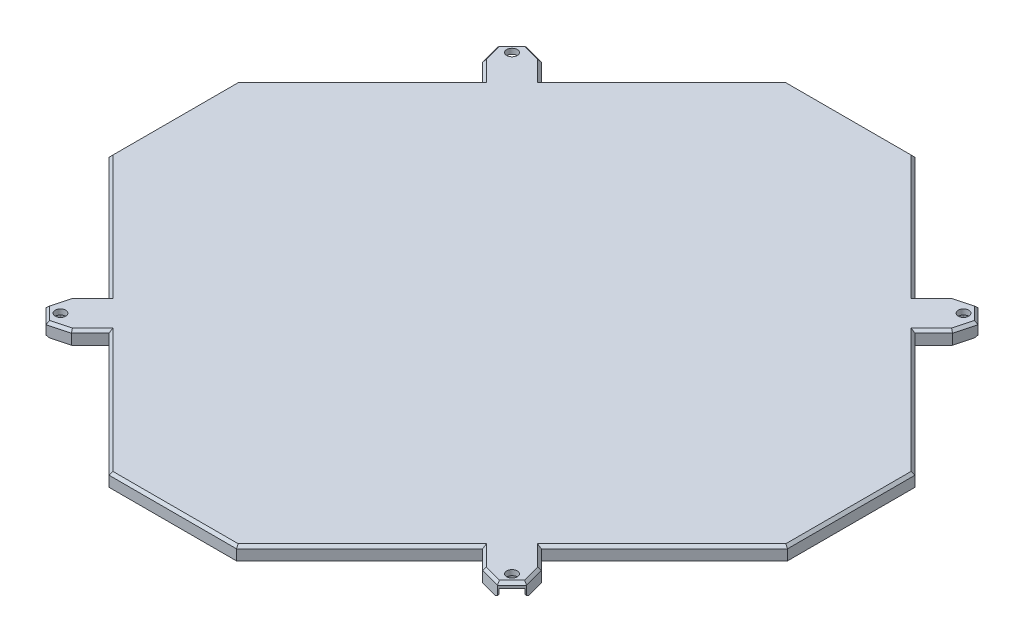
SolidWorks part; units mm, degrees
ref_plane "Front Plane" through (0, 0, 0) normal (0, 0, 1) x (1, 0, 0)
ref_plane "Top Plane" through (0, 0, 0) normal (0, 1, 0) x (1, 0, 0)
ref_plane "Right Plane" through (0, 0, 0) normal (1, 0, 0) x (0, 0, -1)
sketch "Floor Reference" plane through (0, 0, 0) normal (0, 1, 0) x (-1, 0, 0)
  line L0 (-129.3223, 24.3223) -> (-82.4792, 71.1655)
  line L1 (-82.4792, 71.1655) -> (-89.601, 78.2873)
  line L2 (-89.601, 78.2873) -> (-91.6716, 86.0147)
  line L3 (-91.6716, 86.0147) -> (-86.0147, 91.6716)
  line L4 (-86.0147, 91.6716) -> (-78.2873, 89.601)
  line L5 (-78.2873, 89.601) -> (-71.1655, 82.4792)
  line L6 (-71.1655, 82.4792) -> (-24.3223, 129.3223)
  line L7 (-24.3223, 129.3223) -> (0, 129.3223)
  line L31 (-129.3223, 0) -> (-129.3223, 24.3223)
  line L32 (0, 0) -> (-35355.3391, 35355.3391) construction
  line L34 (-1000, 0) -> (0, 0) construction
  line L35 (0, 0) -> (0, 49000) construction
  circle A0 centre (-86.0147, 86.0147) radius 2
  point P8 (0, 0)
  point P14 (0, 0)
  point P18 (-88.8431, 88.8431)
  dimension "D11" = 4
  dimension "D1" = 105
  dimension "D2" = 45
  dimension "D3" = 129.3223
  dimension "D4" = 8
  dimension "D5" = 16
  dimension "D6" = 17
  dimension "D7" = 8
  dimension "D8" = 13
  dimension "D9" = 105
  dimension "D10" = 24.3223
sketch "Sketch2" plane through (0, 0, 0) normal (0, 1, 0) x (1, 0, 0)
  line L0 (129.3223, 0) -> (129.3223, -24.3223) construction
  line L1 (129.3223, -24.3223) -> (82.4792, -71.1655) construction
  line L2 (82.4792, -71.1655) -> (89.601, -78.2873) construction
  line L3 (89.601, -78.2873) -> (91.6716, -86.0147) construction
  line L4 (91.6716, -86.0147) -> (86.0147, -91.6716) construction
  line L5 (86.0147, -91.6716) -> (78.2873, -89.601) construction
  line L6 (78.2873, -89.601) -> (71.1655, -82.4792) construction
  line L7 (71.1655, -82.4792) -> (24.3223, -129.3223) construction
  line L8 (24.3223, -129.3223) -> (0, -129.3223) construction
  line L9 (129.3223, 0) -> (129.3223, -24.3223) construction
  line L10 (129.3223, -24.3223) -> (82.4792, -71.1655) construction
  line L11 (82.4792, -71.1655) -> (89.601, -78.2873) construction
  line L12 (89.601, -78.2873) -> (91.6716, -86.0147) construction
  line L13 (91.6716, -86.0147) -> (86.0147, -91.6716) construction
  line L14 (86.0147, -91.6716) -> (78.2873, -89.601) construction
  line L15 (78.2873, -89.601) -> (71.1655, -82.4792) construction
  line L16 (71.1655, -82.4792) -> (24.3223, -129.3223) construction
  line L17 (24.3223, -129.3223) -> (0, -129.3223) construction
  line L18 (-129.3223, -24.3223) -> (-129.3223, 0) construction
  line L19 (-82.4792, -71.1655) -> (-129.3223, -24.3223) construction
  line L20 (-89.601, -78.2873) -> (-82.4792, -71.1655) construction
  line L21 (-91.6716, -86.0147) -> (-89.601, -78.2873) construction
  line L22 (-86.0147, -91.6716) -> (-91.6716, -86.0147) construction
  line L23 (-78.2873, -89.601) -> (-86.0147, -91.6716) construction
  line L24 (-71.1655, -82.4792) -> (-78.2873, -89.601) construction
  line L25 (-24.3223, -129.3223) -> (-71.1655, -82.4792) construction
  line L26 (0, -129.3223) -> (-24.3223, -129.3223) construction
  line L27 (-24.3223, 129.3223) -> (0, 129.3223) construction
  line L28 (-71.1655, 82.4792) -> (-24.3223, 129.3223) construction
  line L29 (-78.2873, 89.601) -> (-71.1655, 82.4792) construction
  line L30 (-86.0147, 91.6716) -> (-78.2873, 89.601) construction
  line L31 (-91.6716, 86.0147) -> (-86.0147, 91.6716) construction
  line L32 (-89.601, 78.2873) -> (-91.6716, 86.0147) construction
  line L33 (-82.4792, 71.1655) -> (-89.601, 78.2873) construction
  line L34 (-129.3223, 24.3223) -> (-82.4792, 71.1655) construction
  line L35 (-129.3223, 0) -> (-129.3223, 24.3223) construction
  line L36 (129.3223, 24.3223) -> (129.3223, 0) construction
  line L37 (82.4792, 71.1655) -> (129.3223, 24.3223) construction
  line L38 (89.601, 78.2873) -> (82.4792, 71.1655) construction
  line L39 (91.6716, 86.0147) -> (89.601, 78.2873) construction
  line L40 (86.0147, 91.6716) -> (91.6716, 86.0147) construction
  line L41 (78.2873, 89.601) -> (86.0147, 91.6716) construction
  line L42 (71.1655, 82.4792) -> (78.2873, 89.601) construction
  line L43 (24.3223, 129.3223) -> (71.1655, 82.4792) construction
  line L44 (0, 129.3223) -> (24.3223, 129.3223) construction
  line L45 (129.2223, 0) -> (129.2223, -24.2809)
  line L46 (129.2223, -24.2809) -> (82.3378, -71.1655)
  line L47 (82.3378, -71.1655) -> (89.5114, -78.3391)
  line L48 (89.5114, -78.3391) -> (91.56, -85.9848)
  line L49 (91.56, -85.9848) -> (85.9848, -91.56)
  line L50 (85.9848, -91.56) -> (78.3391, -89.5114)
  line L51 (78.3391, -89.5114) -> (71.1655, -82.3378)
  line L52 (71.1655, -82.3378) -> (24.2809, -129.2223)
  line L53 (24.2809, -129.2223) -> (0, -129.2223)
  line L54 (0, -129.2223) -> (-24.2809, -129.2223)
  line L55 (-24.2809, -129.2223) -> (-71.1655, -82.3378)
  line L56 (-71.1655, -82.3378) -> (-78.3391, -89.5114)
  line L57 (-78.3391, -89.5114) -> (-85.9848, -91.56)
  line L58 (-85.9848, -91.56) -> (-91.56, -85.9848)
  line L59 (-91.56, -85.9848) -> (-89.5114, -78.3391)
  line L60 (-89.5114, -78.3391) -> (-82.3378, -71.1655)
  line L61 (-82.3378, -71.1655) -> (-129.2223, -24.2809)
  line L62 (-129.2223, -24.2809) -> (-129.2223, 0)
  line L63 (-129.2223, 0) -> (-129.2223, 24.2809)
  line L64 (-129.2223, 24.2809) -> (-82.3378, 71.1655)
  line L65 (-82.3378, 71.1655) -> (-89.5114, 78.3391)
  line L66 (-89.5114, 78.3391) -> (-91.56, 85.9848)
  line L67 (-91.56, 85.9848) -> (-85.9848, 91.56)
  line L68 (-85.9848, 91.56) -> (-78.3391, 89.5114)
  line L69 (-78.3391, 89.5114) -> (-71.1655, 82.3378)
  line L70 (-71.1655, 82.3378) -> (-24.2809, 129.2223)
  line L71 (-24.2809, 129.2223) -> (0, 129.2223)
  line L72 (0, 129.2223) -> (24.2809, 129.2223)
  line L73 (24.2809, 129.2223) -> (71.1655, 82.3378)
  line L74 (71.1655, 82.3378) -> (78.3391, 89.5114)
  line L75 (78.3391, 89.5114) -> (85.9848, 91.56)
  line L76 (85.9848, 91.56) -> (91.56, 85.9848)
  line L77 (91.56, 85.9848) -> (89.5114, 78.3391)
  line L78 (89.5114, 78.3391) -> (82.3378, 71.1655)
  line L79 (82.3378, 71.1655) -> (129.2223, 24.2809)
  line L80 (129.2223, 24.2809) -> (129.2223, 0)
  circle A0 centre (86.0147, -86.0147) radius 2 construction
  circle A1 centre (86.0147, -86.0147) radius 2
  circle A2 centre (-86.0147, -86.0147) radius 2
  circle A3 centre (-86.0147, 86.0147) radius 2
  circle A4 centre (86.0147, 86.0147) radius 2
  point P13 (0, 0)
  point P54 (0, 0)
  dimension "D2" = 0.1
  dimension "D1" = 4
extrude "Main Floor Extrude" add sketch "Sketch2" along normal blind 5
chamfer "Main Floor Chamfer" distance 1 angle 45 32 edges at (-74.7523, 5, -85.9246) (-82.162, 5, -90.5357) (-88.7724, 5, -88.7724) (-90.5357, 5, -82.162) (-85.9246, 5, -74.7523) (-47.7232, 5, -105.78) (0, 5, -129.2223) (47.7232, 5, -105.78) (74.7523, 5, -85.9246) (82.162, 5, -90.5357) (88.7724, 5, -88.7724) (90.5357, 5, -82.162) (85.9246, 5, -74.7523) (105.78, 5, -47.7232) (129.2223, 5, 0) (105.78, 5, 47.7232) (85.9246, 5, 74.7523) (90.5357, 5, 82.162) (88.7724, 5, 88.7724) (82.162, 5, 90.5357) (74.7523, 5, 85.9246) (47.7232, 5, 105.78) (0, 5, 129.2223) (-47.7232, 5, 105.78) (-74.7523, 5, 85.9246) (-82.162, 5, 90.5357) (-88.7724, 5, 88.7724) (-90.5357, 5, 82.162) (-85.9246, 5, 74.7523) (-105.78, 5, 47.7232) (-129.2223, 5, 0) (-105.78, 5, -47.7232)
sketch "Sketch3" plane through (0, 0, 0) normal (0, -1, 0) x (-1, 0, 0)
  line L0 (91.2473, -86.2976) -> (88.4896, -83.5398)
  line L1 (91.56, -85.9848) -> (85.9848, -91.56) construction
  line L2 (83.5398, -88.4896) -> (86.2976, -91.2473)
  line L3 (86.2976, -91.2473) -> (91.2473, -86.2976)
  line L4 (-86.2976, -91.2473) -> (-83.5398, -88.4896)
  line L5 (-88.4896, -83.5398) -> (-91.2473, -86.2976)
  line L6 (-91.2473, -86.2976) -> (-86.2976, -91.2473)
  line L7 (-91.2473, 86.2976) -> (-88.4896, 83.5398)
  line L8 (-83.5398, 88.4896) -> (-86.2976, 91.2473)
  line L9 (-86.2976, 91.2473) -> (-91.2473, 86.2976)
  line L10 (86.2976, 91.2473) -> (83.5398, 88.4896)
  line L11 (88.4896, 83.5398) -> (91.2473, 86.2976)
  line L12 (91.2473, 86.2976) -> (86.2976, 91.2473)
  arc A0 (88.4896, -83.5398) -> (83.5398, -88.4896) centre (86.0147, -86.0147) ccw
  arc A1 (83.5398, -88.4896) -> (88.4896, -83.5398) centre (86.0147, -86.0147) ccw construction
  arc A2 (-83.5398, -88.4896) -> (-88.4896, -83.5398) centre (-86.0147, -86.0147) ccw
  arc A3 (-88.4896, -83.5398) -> (-83.5398, -88.4896) centre (-86.0147, -86.0147) ccw construction
  arc A4 (-88.4896, 83.5398) -> (-83.5398, 88.4896) centre (-86.0147, 86.0147) ccw
  arc A5 (-83.5398, 88.4896) -> (-88.4896, 83.5398) centre (-86.0147, 86.0147) ccw construction
  arc A6 (83.5398, 88.4896) -> (88.4896, 83.5398) centre (86.0147, 86.0147) ccw
  arc A7 (88.4896, 83.5398) -> (83.5398, 88.4896) centre (86.0147, 86.0147) ccw construction
  point P1 (0, 0)
  point P9 (0, 0)
  point P10 (86.0147, 91.2473)
  point P28 (0, 0)
  dimension "D1" = 7
  dimension "D2" = 4
extrude "Mount Screw Countersink" cut sketch "Sketch3" against normal blind 3
chamfer "Mount Screw Countersink Chamfer" distance 1 angle 45 12 edges at (-84.9187, 0, -89.8685) (-89.8685, 0, -84.9187) (-83.5398, 0, -83.5398) (89.8685, 0, -84.9187) (84.9187, 0, -89.8685) (83.5398, 0, -83.5398) (84.9187, 0, 89.8685) (89.8685, 0, 84.9187) (83.5398, 0, 83.5398) (-89.8685, 0, 84.9187) (-84.9187, 0, 89.8685) (-83.5398, 0, 83.5398)
